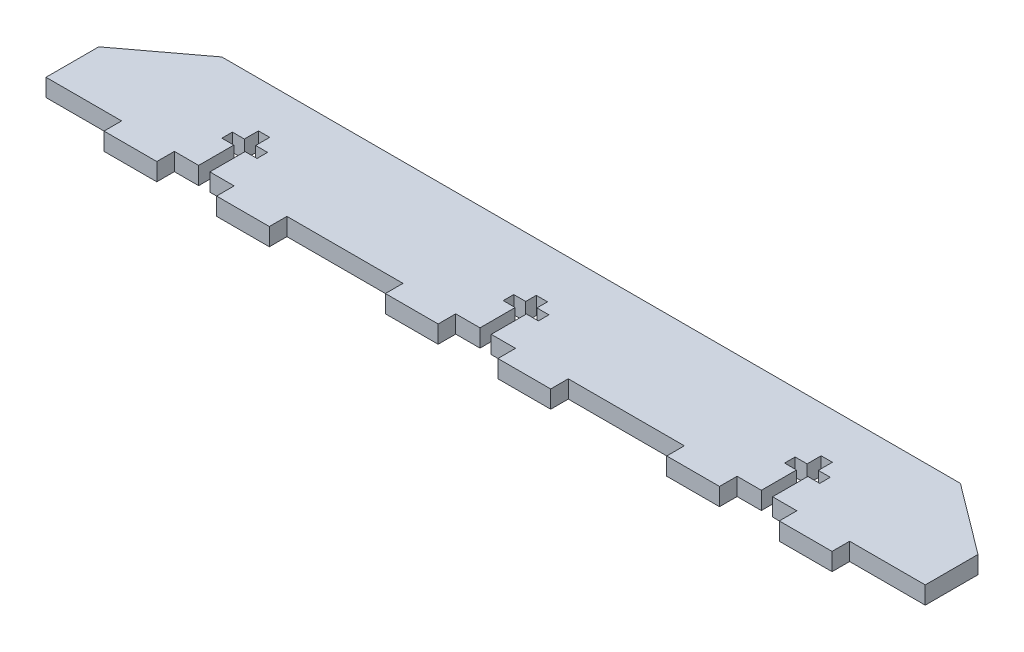
SolidWorks part; units mm, degrees
ref_plane "前基準面" through (0, 0, 0) normal (0, 0, 1) x (1, 0, 0)
ref_plane "上基準面" through (0, 0, 0) normal (0, 1, 0) x (1, 0, 0)
ref_plane "右基準面" through (0, 0, 0) normal (1, 0, 0) x (0, 0, -1)
sketch "草圖1" plane through (0, 0, 0) normal (0, 1, 0) x (1, 0, 0)
  line L0 (0, 40.8343) -> (0, -34.8752) construction
  line L1 (-125, -15) -> (-103.5, -15)
  line L2 (-125, -15) -> (-125, 0)
  line L3 (-105, 15) -> (105, 15)
  line L4 (125, -15) -> (125, 0)
  line L5 (-125, -15) -> (125, 15) construction
  line L6 (-125, 15) -> (125, -15) construction
  line L7 (-55, 15) -> (-105, 15) construction
  line L8 (-80, 15) -> (-80, -25.1868) construction
  line L9 (-103.5, -15) -> (-103.5, -20)
  line L10 (-103.5, -20) -> (-88.5, -20)
  line L11 (-88.5, -20) -> (-88.5, -15)
  line L12 (-81.6, -15) -> (-81.6, -5)
  line L13 (-81.6, -5) -> (-85, -5)
  line L14 (-85, -5) -> (-85, -2)
  line L15 (-85, -2) -> (-81.6, -2)
  line L16 (-81.6, -2) -> (-81.6, 2)
  line L17 (-81.6, 2) -> (-78.4, 2)
  line L18 (-96, -20) -> (-96, -5.8111) construction
  line L19 (-56.5, -15) -> (-56.5, -20)
  line L20 (-56.5, -20) -> (-71.5, -20)
  line L21 (-71.5, -20) -> (-71.5, -15)
  line L22 (-78.4, -15) -> (-78.4, -5)
  line L23 (-78.4, -2) -> (-78.4, 2)
  line L24 (-75, -2) -> (-78.4, -2)
  line L25 (-75, -5) -> (-75, -2)
  line L26 (-78.4, -5) -> (-75, -5)
  line L27 (-78.4, -15) -> (-71.5, -15)
  line L28 (-88.5, -15) -> (-81.6, -15)
  line L29 (-56.5, -15) -> (-23.5, -15)
  line L30 (81.6, -5) -> (85, -5)
  line L31 (85, -5) -> (85, -2)
  line L32 (85, -2) -> (81.6, -2)
  line L33 (81.6, -2) -> (81.6, 2)
  line L34 (81.6, 2) -> (78.4, 2)
  line L35 (75, -2) -> (78.4, -2)
  line L36 (78.4, -2) -> (78.4, 2)
  line L37 (75, -5) -> (75, -2)
  line L38 (78.4, -5) -> (75, -5)
  line L39 (78.4, -15) -> (78.4, -5)
  line L40 (81.6, -15) -> (81.6, -5)
  line L41 (103.5, -15) -> (103.5, -20)
  line L42 (103.5, -20) -> (88.5, -20)
  line L43 (88.5, -20) -> (88.5, -15)
  line L44 (71.5, -20) -> (71.5, -15)
  line L45 (56.5, -20) -> (71.5, -20)
  line L46 (56.5, -15) -> (56.5, -20)
  line L47 (71.5, -15) -> (78.4, -15)
  line L48 (81.6, -15) -> (88.5, -15)
  line L49 (103.5, -15) -> (125, -15)
  line L50 (-23.5, -15) -> (-23.5, -20)
  line L51 (-23.5, -20) -> (-8.5, -20)
  line L52 (-8.5, -20) -> (-8.5, -15)
  line L53 (-1.6, -15) -> (-1.6, -5)
  line L54 (-1.6, -5) -> (-5, -5)
  line L55 (-5, -5) -> (-5, -2)
  line L56 (-5, -2) -> (-1.6, -2)
  line L57 (-1.6, -2) -> (-1.6, 1)
  line L58 (-1.6, 1) -> (1.6, 1)
  line L59 (-16, -20) -> (-16, -9.7697) construction
  line L60 (23.5, -15) -> (23.5, -20)
  line L61 (23.5, -20) -> (8.5, -20)
  line L62 (8.5, -20) -> (8.5, -15)
  line L63 (1.6, -15) -> (1.6, -5)
  line L64 (1.6, -5) -> (5, -5)
  line L65 (5, -5) -> (5, -2)
  line L66 (5, -2) -> (1.6, -2)
  line L67 (1.6, -2) -> (1.6, 1)
  line L68 (-8.5, -15) -> (-1.6, -15)
  line L69 (1.6, -15) -> (8.5, -15)
  line L70 (23.5, -15) -> (56.5, -15)
  line L71 (-105, 15) -> (-125, 0)
  line L72 (105, 15) -> (125, 0)
  point P0 (0, 0)
  point P29 (-80, 2)
  point P77 (0, 1)
  dimension "D1" = 250
  dimension "D2" = 30
  dimension "D3" = 15
  dimension "D4" = 5
  dimension "D5" = 16
  dimension "D6" = 10
  dimension "D7" = 3.4
  dimension "D8" = 3.4
  dimension "D9" = 3
  dimension "D10" = 4
  dimension "D11" = 3.2
  dimension "D12" = 80
  dimension "D13" = 15
  dimension "D14" = 5
  dimension "D15" = 16
  dimension "D16" = 10
  dimension "D17" = 3.4
  dimension "D18" = 3.4
  dimension "D19" = 3
  dimension "D20" = 3
  dimension "D21" = 3.2
  dimension "D22" = 20
  dimension "D23" = 15
extrude "填料-伸長1" add sketch "草圖1" along normal blind 5
